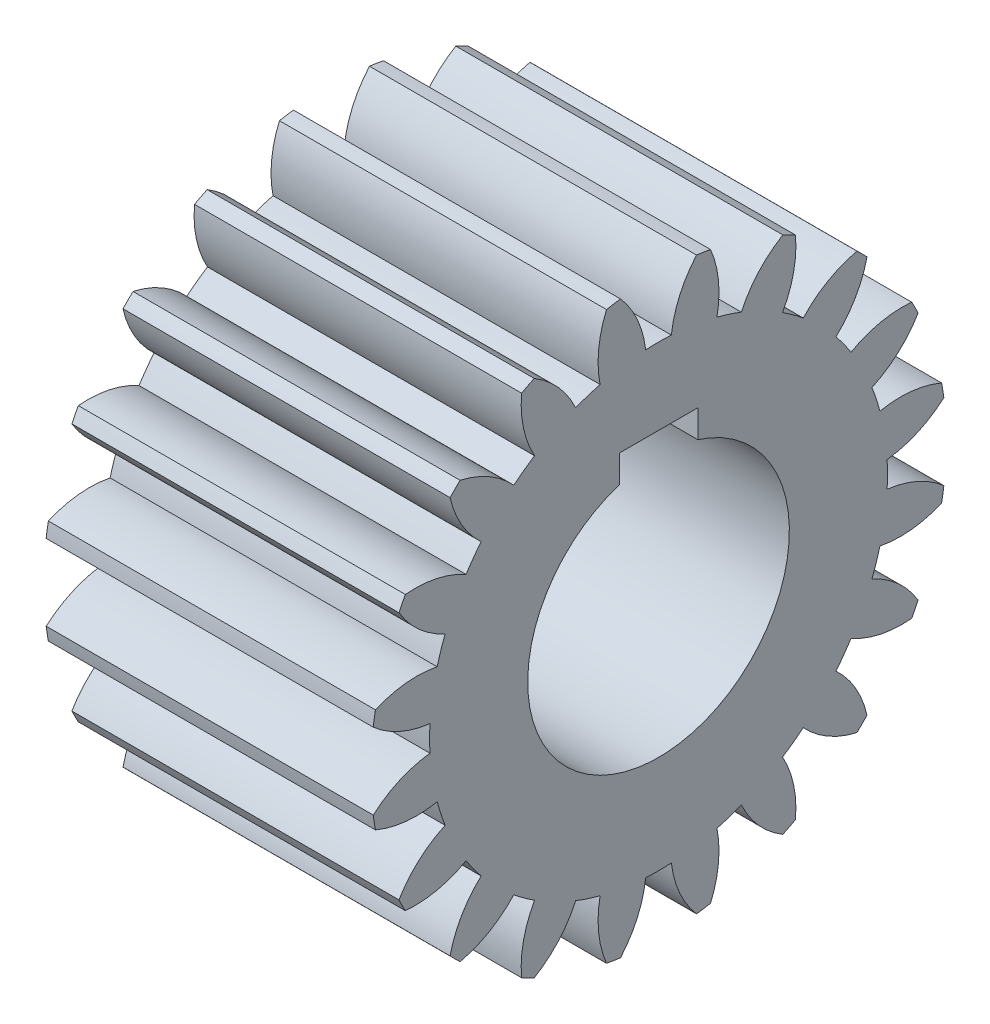
SolidWorks part; units mm, degrees
ref_plane "Plane1" through (0, 0, 0) normal (0, 0, 1) x (1, 0, 0)
ref_plane "Plane2" through (0, 0, 0) normal (0, 1, 0) x (1, 0, 0)
ref_plane "Plane3" through (0, 0, 0) normal (1, 0, 0) x (0, 0, -1)
other "Configuration Table"
sketch "HoldingSke" plane through (0, 0, 0) normal (0, 1, 0) x (1, 0, 0)
  line L0 (0, 0) -> (0.2349, -0.0855)
  line L1 (-15, 0) -> (100, 0) construction
  line L2 (0, 0) -> (-2.1039, 2.3779)
  line L3 (0, 0) -> (-11.863, 4.5341)
  line L4 (0, 0) -> (8.1152, 2.9537)
  line L5 (0, 0) -> (-46.8476, -17.4728)
  line L6 (0, 0) -> (-41.4481, -27.9652)
  line L7 (-2.1039, 2.3779) -> (8.6586, 51.2059)
  line L8 (-76.2, 54.61) -> (-72.9, 54.61)
  line L9 (-71.009, 38.7566) -> (-53.1078, 45.2721)
  line L10 (-76.2, 71.12) -> (104.1128, 71.12)
  line L11 (0, 0) -> (-50, 0)
  line L12 (-76.2, 101.6) -> (-76.073, 101.6)
  line L13 (24.9733, 27.94) -> (52.9518, 28.4284)
  line L14 (24.9733, 27.94) -> (24.9743, 27.94)
  line L15 (24.9733, 27.94) -> (100.4006, 29.5858)
  line L16 (-63.627, -4) -> (-12.827, -4)
  circle A0 centre (0, 0) radius 20
  circle A1 centre (0, 0) radius 34.999
  circle A2 centre (0, 0) radius 37.5
  circle A3 centre (0, 0) radius 20
  dimension "Hub_dia" = 75
  dimension "Pitch" = 0.25
  dimension "Overall_len" = 50
  dimension "T_dim" = 3.3
  dimension "Ap" = 20
  dimension "H" = 19.05
  dimension "Pitch_radius" = 180.3128
  dimension "Backlash" = 0.127
  dimension "Addendum_fac" = 1
  dimension "Dedendum_fac" = 1.25
  dimension "Clearance_fac" = 0.25
  dimension "Dedendum_add" = 0.001
  dimension "Module" = 4
sketch "BasProSke" plane through (0, 0, 0) normal (0, 1, 0) x (1, 0, 0)
  line L0 (-10, 0) -> (60, 0) construction
  line L1 (0, 0) -> (0, 44)
  line L2 (0, 0) -> (50, 0)
  line L3 (50, 0) -> (50, 44)
  line L4 (50, 44) -> (0, 44)
revolve "Base-Revolve" add sketch "BasProSke" angle 360 about L0
sketch "TooCutSke" plane through (0, 0, 0) normal (1, 0, 0) x (0, 0, -1)
  line L1 (0, 0) -> (0, 107) construction
  line L2 (0, 0) -> (-3.3605, 39.8586) construction
  line L3 (0, 0) -> (-12.4815, 78.8048) construction
  line L4 (-3.3605, 39.8586) -> (-6.2407, 39.4024) construction
  arc A0 (1.9617, 34.944) -> (-1.9617, 34.944) centre (0, 0) ccw
  arc A1 (5.8321, 43.6374) -> (-5.8321, 43.6374) centre (0, 0) ccw
  circle A2 centre (0, 0) radius 40 construction
  circle A3 centre (0, 0) radius 37.5877 construction
  arc A4 (-1.9617, 34.944) -> (-5.8321, 43.6374) centre (-17.8525, 33.0775) ccw
  arc A5 (5.8321, 43.6374) -> (1.9617, 34.944) centre (17.8525, 33.0775) ccw
extrude "ToothCut" cut sketch "TooCutSke" along normal through all
fillet "Breaks" [suppressed] radius 0.08
fillet "RootFillets" [suppressed] radius 1.001
pattern_circular "TeethCuts" count 20 every 18 about axis through (-10, 0, 0) along (1, 0, 0) of "ToothCut", "RootFillets", "Breaks"
sketch "HubNeaOneSke" plane through (0, 0, 0) normal (-1, 0, 0) x (0, 0, 1)
  circle A0 centre (0, 0) radius 34.999
extrude "HubNearOne" [suppressed] add sketch "HubNeaOneSke" along normal blind 20.0001
sketch "HubNeaBotSke" plane through (0, 0, 0) normal (-1, 0, 0) x (0, 0, 1)
  circle A0 centre (0, 0) radius 34.999
extrude "HubNearBoth" [suppressed] add sketch "HubNeaBotSke" along normal blind 10
ref_plane "FarPln" through (50, 0, 0) normal (1, 0, 0) x (0, 0, -1)
sketch "HubFarSke" plane through (50, 0, 0) normal (1, 0, 0) x (0, 0, -1)
  circle A0 centre (0, 0) radius 34.999
extrude "HubFar" [suppressed] add sketch "HubFarSke" along normal blind 10
sketch "BorSke" plane through (0, 0, 0) normal (1, 0, 0) x (0, 0, -1)
  circle A0 centre (0, 0) radius 20
extrude "Bore" cut sketch "BorSke" along normal mid plane 100.0001
sketch "KeySke" plane through (0, 0, 0) normal (1, 0, 0) x (0, 0, -1)
  line L0 (-6, 0) -> (-6, 23.3)
  line L1 (-6, 23.3) -> (6, 23.3)
  line L2 (6, 23.3) -> (6, 0)
  line L3 (0, 0) -> (0, 34) construction
  line L4 (-6, 0) -> (6, 0)
extrude "Keyway" cut sketch "KeySke" along normal mid plane 100.0001
pattern_circular "Keyway2" [suppressed] count 2 every 90 about axis through (-10, 0, 0) along (1, 0, 0)
equation "' \"Module@HoldingSke\" = 6.35"
equation "' \"Num_teeth@HoldingSke\" = 12"
equation "' \"Ap@HoldingSke\" =  20"
equation "' \"Ap@HoldingSke\" = 20"
equation "' \"Width@HoldingSke\" = 0.5 * 25.4"
equation "' \"Hub_dia@HoldingSke\"= 1 * 25.4"
equation "' \"Hub_dia@HoldingSke\" = 1 * 25.4"
equation "' \"Overall_len@HoldingSke\" = 1.0 * 25.4"
equation "' \"Bore@HoldingSke\" = 0.75 * 25.4"
equation "' \"T_dim@HoldingSke\" = 0.1 * 25.4"
equation "' \"Width@KeySke\" = 0.25 * 25.4"
equation "' \"Show_teeth@HoldingSke\" = 13"
equation "' \"Backlash@HoldingSke\" = 0.009 * 25.4"
equation "' \"Addendum_fac@HoldingSke\" = 1.0"
equation "' \"Dedendum_fac@HoldingSke\" = 1.25"
equation "' \"Dedendum_add@HoldingSke\" = 0.00005 * 25.4"
equation "' \"Clearance_fac@HoldingSke\" = 0.25"
equation "\"Pitch@HoldingSke\" = 1 / \"Module@HoldingSke\""
equation "\"Overcut_dia@TooCutSke\" = (\"Num_teeth@HoldingSke\" + 2 * \"Addendum_fac@HoldingSke\") / \"Pitch@HoldingSke\" + 0.002 * 25.4"
equation "\"Pitch_dia@TooCutSke\" = \"Num_teeth@HoldingSke\" / \"Pitch@HoldingSke\""
equation "\"Base_dia@TooCutSke\" = \"Num_teeth@HoldingSke\" / \"Pitch@HoldingSke\" * cos((\"Ap@HoldingSke\"  * 3.14159265 / 180))"
equation "\"Root_dia@TooCutSke\" = (\"Num_teeth@HoldingSke\" + 2) / \"Pitch@HoldingSke\" - 2 * (\"Addendum_fac@HoldingSke\" + \"Dedendum_fac@HoldingSke\") / \"Pitch@HoldingSke\" - \"Dedendum_add@HoldingSke\" * 2"
equation "\"Half_ang@TooCutSke\" = 180 / \"Num_teeth@HoldingSke\""
equation "\"Half_CT@TooCutSke\" = \"Num_teeth@HoldingSke\" / \"Pitch@HoldingSke\" * sin((3.14159265 / 2 / \"Num_teeth@HoldingSke\")) / 2 - 7 * \"Backlash@HoldingSke\" / 4"
equation "\"Flank_rad@TooCutSke\" = \"Num_teeth@HoldingSke\" / \"Pitch@HoldingSke\" / 5"
equation "\"Radius@RootFillets\" = \"Clearance_fac@HoldingSke\" / \"Pitch@HoldingSke\" + \"Dedendum_add@HoldingSke\""
equation "\"Break_rad@Breaks\" = 0.02 / \"Pitch@HoldingSke\""
equation "\"Thickness@HoldingSke\" = \"Width@HoldingSke\""
equation "\"OAL@HoldingSke\" = \"Thickness@HoldingSke\""
equation "\"MHD@HoldingSke\" = (\"Num_teeth@HoldingSke\" + 2) / \"Pitch@HoldingSke\" - 2 * (\"Addendum_fac@HoldingSke\" + \"Dedendum_fac@HoldingSke\")  / \"Pitch@HoldingSke\" - \"Dedendum_add@HoldingSke\" * 2"
equation "\"MBD@HoldingSke\" = (\"Num_teeth@HoldingSke\" + 2) / \"Pitch@HoldingSke\" - 2 * (\"Addendum_fac@HoldingSke\" + \"Dedendum_fac@HoldingSke\")  / \"Pitch@HoldingSke\" - \"Dedendum_add@HoldingSke\" * 2 - 0.002 * 25.4"
equation "\"MHD@HoldingSke\" = ((sgn( \"MHD@HoldingSke\" - \"Hub_dia@HoldingSke\" )-1)*( \"MHD@HoldingSke\" - \"Hub_dia@HoldingSke\" ))/-2+ \"Hub_dia@HoldingSke\""
equation "\"MBD@HoldingSke\" = ((sgn( \"MBD@HoldingSke\" - \"Bore@HoldingSke\" )-1)*( \"MBD@HoldingSke\" - \"Bore@HoldingSke\" ))/-2+ \"Bore@HoldingSke\""
equation "\"OAL@HoldingSke\" = ((sgn( \"OAL@HoldingSke\" - \"Overall_len@HoldingSke\" )+1)*( \"OAL@HoldingSke\" - \"Overall_len@HoldingSke\" ))/2 + \"Overall_len@HoldingSke\" + 0.000002 * 25.4"
equation "\"Num_teeth@TeethCuts\" = int( \"Show_teeth@HoldingSke\" ) + 1"
equation "\"Num_teeth@TeethCuts\" = ((sgn( \"Num_teeth@TeethCuts\" - \"Num_teeth@HoldingSke\" )-1)*( \"Num_teeth@TeethCuts\" - \"Num_teeth@HoldingSke\" ))/-2+ \"Num_teeth@HoldingSke\""
equation "\"Num_teeth@TeethCuts\" = ((sgn( \"Num_teeth@TeethCuts\" - 2.0)+1)*( \"Num_teeth@TeethCuts\" - 2.0))/2 +2.0"
equation "\"Angle@TeethCuts\" = 360.0 / \"Num_teeth@HoldingSke\""
equation "\"Diameter@BasProSke\" = (\"Num_teeth@HoldingSke\" + 2 * \"Addendum_fac@HoldingSke\") / \"Pitch@HoldingSke\""
equation "\"Thickness@BasProSke\"  = \"Thickness@HoldingSke\""
equation "' \"Fillet_rad@BasProSke\" =  \"Thickness@HoldingSke\" * 0.05"
equation "' \"Fillet_rad@BasProSke\" = \"Thickness@HoldingSke\" * 0.05"
equation "\"MHD@HoldingSke\" = ((sgn( \"MHD@HoldingSke\" - \"Root_dia@TooCutSke\" )-1)*( \"MHD@HoldingSke\" - \"Root_dia@TooCutSke\" ))/-2+ \"Root_dia@TooCutSke\""
equation "\"Diameter@HubNeaOneSke\" = \"MHD@HoldingSke\""
equation "\"Length@HubNearOne\" = \"OAL@HoldingSke\" - \"Thickness@BasProSke\""
equation "\"Diameter@HubNeaBotSke\" = \"MHD@HoldingSke\""
equation "\"Length@HubNearBoth\" = ( \"OAL@HoldingSke\" - \"Thickness@BasProSke\" ) / 2.0"
equation "\"Thickness@FarPln\" = \"Thickness@BasProSke\""
equation "\"Diameter@HubFarSke\" = \"MHD@HoldingSke\""
equation "\"Length@HubFar\" = ( \"OAL@HoldingSke\" - \"Thickness@BasProSke\" ) / 2.0"
equation "\"Diameter@BorSke\" = \"MBD@HoldingSke\""
equation "\"D1@Bore\" = \"OAL@HoldingSke\" * 2.0"
equation "\"D1@Keyway\" = \"OAL@HoldingSke\" * 2.0"
equation "\"Offset@KeySke\" = \"T_dim@HoldingSke\" + \"MBD@HoldingSke\" / 2.0"
